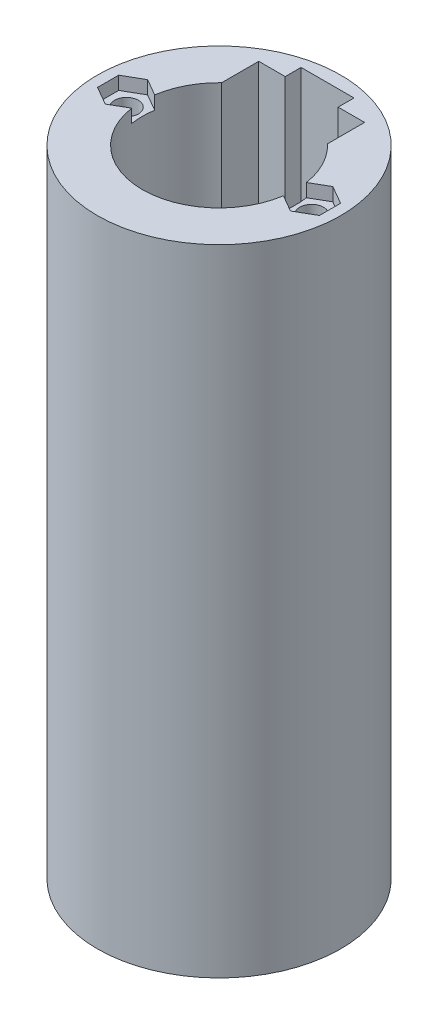
SolidWorks part; units mm, degrees
ref_plane "Front Plane" through (0, 0, 0) normal (0, 0, 1) x (1, 0, 0)
ref_plane "Top Plane" through (0, 0, 0) normal (0, 1, 0) x (1, 0, 0)
ref_plane "Right Plane" through (0, 0, 0) normal (1, 0, 0) x (0, 0, -1)
sketch "Sketch1" plane through (0, 0, 0) normal (0, 1, 0) x (1, 0, 0)
  circle A0 centre (0, 0) radius 23
extrude "Boss-Extrude1" add sketch "Sketch1" along normal blind 120
sketch "Sketch2" plane through (0, 120, 0) normal (0, 1, 0) x (1, 0, 0)
  circle A0 centre (0, 0) radius 14.5
extrude "Cut-Extrude1" cut sketch "Sketch2" against normal blind 120
sketch "Sketch4" plane through (0, 120, 0) normal (0, 1, 0) x (1, 0, 0)
  line L0 (-17.5, 4) -> (-20.9641, 2)
  line L2 (-20.9641, 2) -> (-20.9641, -2)
  line L3 (-20.9641, -2) -> (-17.5, -4)
  line L4 (-17.5, -4) -> (-14.0359, -2)
  line L5 (-14.0359, -2) -> (-14.0359, 2)
  line L6 (14.0359, 2) -> (17.5, 4)
  line L7 (14.0359, -2) -> (14.0359, 2)
  line L8 (17.5, -4) -> (14.0359, -2)
  line L9 (20.9641, -2) -> (17.5, -4)
  line L10 (20.9641, 2) -> (20.9641, -2)
  line L11 (17.5, 4) -> (20.9641, 2)
  line L12 (-14.0359, 2) -> (-17.5, 4)
extrude "Cut-Extrude2" cut sketch "Sketch4" against normal blind 2.5
sketch "Sketch5" plane through (0, 117.5, 0) normal (0, 1, 0) x (1, 0, 0)
  circle A0 centre (-17.5, 0) radius 2.25
  circle A1 centre (17.5, 0) radius 2.25
extrude "Cut-Extrude3" cut sketch "Sketch5" against normal blind 10
sketch "Sketch6" plane through (0, 0, 0) normal (0, -1, 0) x (-1, 0, 0)
  circle A0 centre (0, 0) radius 14.5
extrude "Boss-Extrude2" add sketch "Sketch6" against normal blind 7
sketch "Sketch7" plane through (0, 0, 0) normal (0, -1, 0) x (1, 0, 0)
  circle A0 centre (0, 0) radius 4
extrude "Cut-Extrude4" cut sketch "Sketch7" against normal blind 15
sketch "Sketch8" plane through (0, 120, 0) normal (0, 1, 0) x (1, 0, 0)
  line L5 (-10, 10.5) -> (-10, 17.5)
  line L6 (-10, 17.5) -> (10, 17.5)
  line L7 (10, 17.5) -> (10, 10.5)
  arc A0 (10, 10.5) -> (-10, 10.5) centre (0, 0) ccw
extrude "Cut-Extrude6" cut sketch "Sketch8" against normal blind 25
sketch "Sketch9" plane through (0, 120, 0) normal (0, 1, 0) x (1, 0, 0)
  line L0 (0, 17.5) -> (-5, 17.5)
  line L1 (10, 17.5) -> (-10, 17.5) construction
  line L2 (10, 17.5) -> (-10, 17.5) construction
  line L3 (0, 17.5) -> (5, 17.5)
  line L4 (-5, 17.5) -> (-5, 20.5)
  line L5 (-5, 20.5) -> (5, 20.5)
  line L6 (5, 20.5) -> (5, 17.5)
extrude "Cut-Extrude7" cut sketch "Sketch9" against normal blind 25
